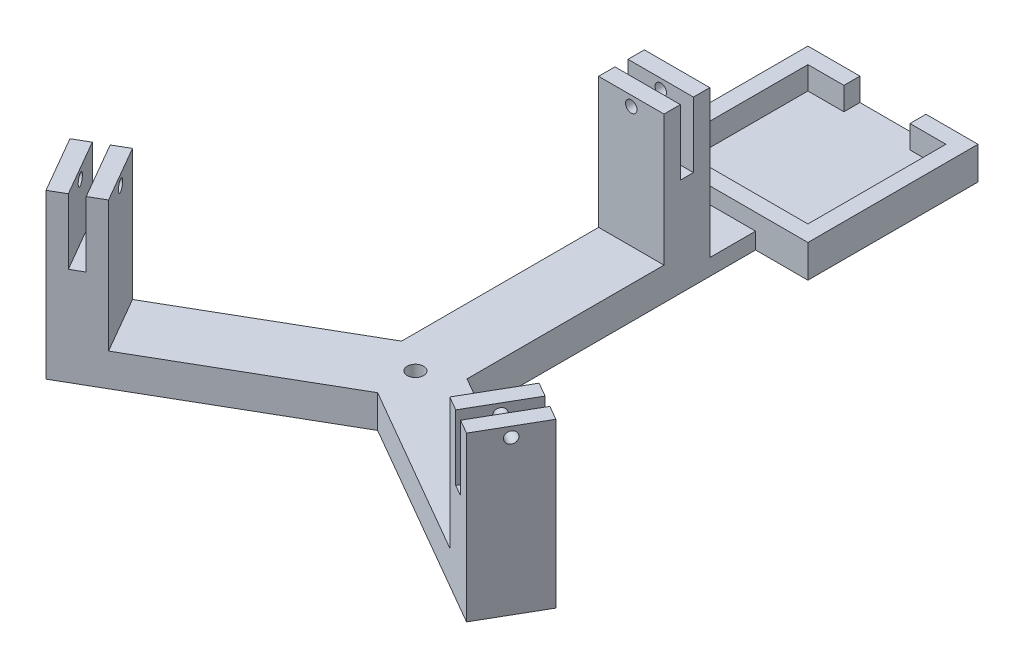
SolidWorks part; units mm, degrees
ref_plane "Front Plane" through (0, 0, 0) normal (0, 0, 1) x (1, 0, 0)
ref_plane "Top Plane" through (0, 0, 0) normal (0, 1, 0) x (1, 0, 0)
ref_plane "Right Plane" through (0, 0, 0) normal (1, 0, 0) x (0, 0, -1)
sketch "Sketch1" plane through (0, 0, 0) normal (0, 1, 0) x (1, 0, 0)
  line L0 (0, 0) -> (-10, 5.7735)
  line L1 (-10, 5.7735) -> (-10, 80)
  line L2 (-10, 80) -> (10, 80)
  line L3 (10, 80) -> (10, 5.7735)
  line L4 (10, 5.7735) -> (0, 0)
  dimension "D1" = 120
  dimension "D2" = 20
  dimension "D3" = 80
extrude "Boss-Extrude1" add sketch "Sketch1" along normal blind 10
sketch "Sketch2" plane through (0, 10, 0) normal (0, 1, 0) x (1, 0, 0)
  line L0 (10, 5.7735) -> (10, 80) construction
  line L1 (-10, 80) -> (10, 80)
  line L2 (-10, 80) -> (-10, 66)
  line L3 (-10, 66) -> (10, 66)
  line L4 (10, 80) -> (10, 66)
  dimension "D1" = 14
extrude "Boss-Extrude2" add sketch "Sketch2" along normal blind 20
sketch "Sketch3" plane through (0, 30, 0) normal (0, 1, 0) x (1, 0, 0)
  line L0 (10, 66) -> (10, 80) construction
  line L1 (-10, 80) -> (10, 80)
  line L2 (-10, 80) -> (-10, 75)
  line L3 (-10, 75) -> (10, 75)
  line L4 (10, 80) -> (10, 75)
  line L6 (-10, 66) -> (10, 66)
  line L7 (-10, 66) -> (-10, 71)
  line L8 (-10, 71) -> (10, 71)
  line L9 (10, 66) -> (10, 71)
  dimension "D1" = 5
  dimension "D2" = 5
extrude "Boss-Extrude3" add sketch "Sketch3" along normal blind 20
sketch "Sketch4" plane through (0, 0, -66) normal (0, 0, 1) x (1, 0, 0)
  line L0 (-10, 50) -> (-10, 10) construction
  line L1 (-10, 50) -> (10, 50) construction
  circle A0 centre (0, 47) radius 1.75
  dimension "D3" = 3.5
  dimension "D1" = 10
  dimension "D2" = 3
extrude "Cut-Extrude1" cut sketch "Sketch4" against normal through all both and the other way through all
pattern_circular "CirPattern1" count 3 over 360 about axis through (0, 0, 0) along (0, 1, 0) of "Boss-Extrude2", "Cut-Extrude1", "Boss-Extrude1", "Boss-Extrude3"
sketch "Sketch5" plane through (0, 10, 0) normal (0, 1, 0) x (1, 0, 0)
  circle A0 centre (0, 0) radius 2.5
  dimension "D1" = 5
extrude "Cut-Extrude2" cut sketch "Sketch5" against normal through all
sketch "Sketch6" plane through (0, 0, 0) normal (0, -1, 0) x (1, 0, 0)
  circle A0 centre (0, 0) radius 2.5 construction
  dimension "D1" = 5
sketch "Sketch8" plane through (0, 0, 0) normal (0, 1, 0) x (1, 0, 0)
  line L10 (-10, 80) -> (10, 80)
  line L11 (-10, 80) -> (-10, 94)
  line L12 (-10, 94) -> (10, 94)
  line L13 (10, 80) -> (10, 94)
  dimension "D2" = 14
  dimension "D13" = 20
sketch "Sketch11" plane through (0, 0, 0) normal (0, 1, 0) x (1, 0, 0)
  line L24 (-26, 146) -> (26, 146)
  line L25 (-26, 94) -> (-26, 146)
  line L26 (26, 146) -> (26, 94)
  line L27 (26, 94) -> (-26, 94)
  line L28 (10, 80) -> (-10, 80) construction
  line L29 (0, 0) -> (0, 94) construction
  dimension "D1" = 52
  dimension "D2" = 52
  dimension "D3" = 14
extrude "Boss-Extrude7" add sketch "Sketch8" along normal blind 5
extrude "Boss-Extrude8" add sketch "Sketch11" along normal blind 10
sketch "Sketch12" plane through (0, 10, 0) normal (0, 1, 0) x (1, 0, 0)
  line L15 (-21.1, 141.1) -> (-10.1, 141.1)
  line L16 (-21.1, 141.1) -> (-21.1, 98.9)
  line L17 (-21.1, 98.9) -> (21.1, 98.9)
  line L18 (21.1, 141.1) -> (21.1, 98.9)
  line L20 (-10.1, 141.1) -> (-10.1, 146)
  line L21 (26, 146) -> (-26, 146) construction
  line L22 (-10.1, 146) -> (10.1, 146)
  line L23 (10.1, 146) -> (10.1, 141.1)
  line L24 (10.1, 141.1) -> (21.1, 141.1)
  line L25 (0, 94) -> (0, 146) construction
  line L26 (-26, 94) -> (26, 94) construction
  dimension "D1" = 42.2
  dimension "D2" = 42.2
  dimension "D3" = 4.9
  dimension "D5" = 11
  dimension "D6" = 11
extrude "Cut-Extrude3" cut sketch "Sketch12" against normal blind 7
